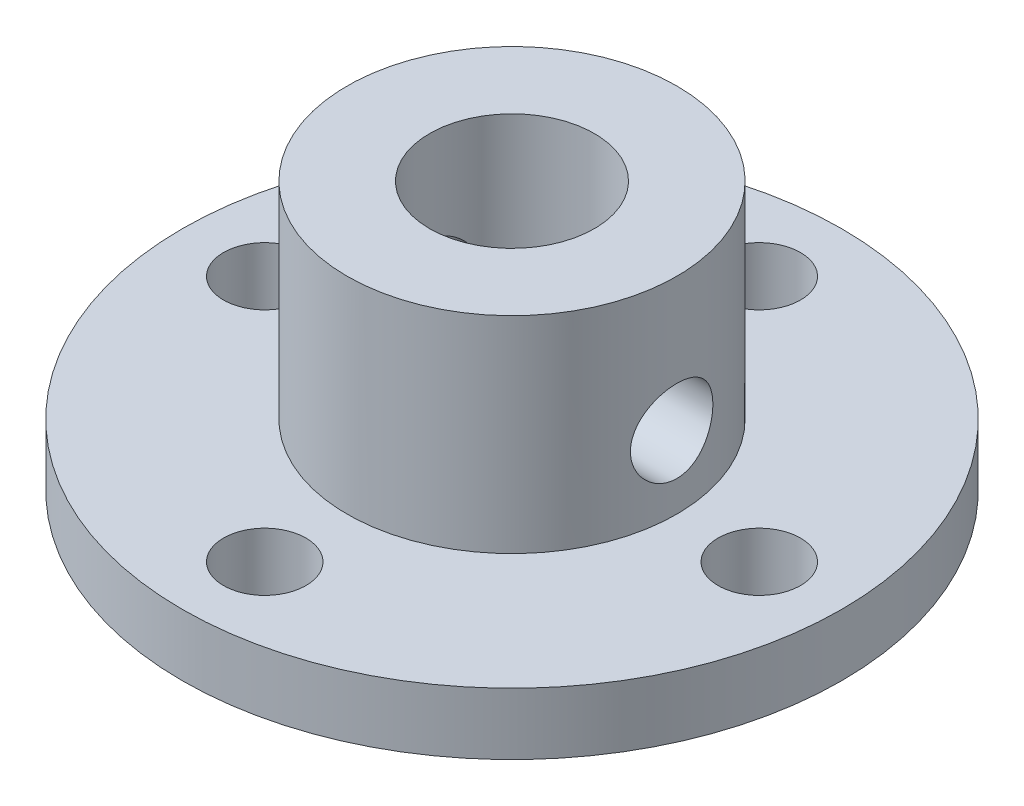
SolidWorks part; units mm, degrees
ref_plane "Front Plane" through (0, 0, 0) normal (0, 0, 1) x (1, 0, 0)
ref_plane "Top Plane" through (0, 0, 0) normal (0, 1, 0) x (1, 0, 0)
ref_plane "Right Plane" through (0, 0, 0) normal (1, 0, 0) x (0, 0, -1)
sketch "Sketch1" plane through (0, 0, 0) normal (0, 1, 0) x (1, 0, 0)
  circle A0 centre (0, 0) radius 4
  circle A1 centre (0, 0) radius 8
  dimension "D1" = 8
  dimension "D2" = 16
extrude "Boss-Extrude1" add sketch "Sketch1" along normal blind 13
sketch "Sketch2" plane through (0, 0, 0) normal (0, -1, 0) x (1, 0, 0)
  line L0 (0, 0) -> (0, 12) construction
  circle A0 centre (0, 0) radius 4
  circle A1 centre (0, 0) radius 16
  circle A2 centre (0, 12) radius 2
  circle A3 centre (12, 0) radius 2
  circle A4 centre (0, -12) radius 2
  circle A5 centre (-12, 0) radius 2
  point P15 (0, 0)
  dimension "D1" = 12
  dimension "D2" = 4
  dimension "D3" = 4
extrude "Boss-Extrude2" add sketch "Sketch2" against normal blind 3
sketch "Sketch4" plane through (0, 13, 0) normal (0, 1, 0) x (1, 0, 0)
  line L0 (0, 4) -> (0, -4) construction
  circle A0 centre (0, 0) radius 4 construction
ref_plane "Plane1" through (0, 0, 0) normal (-1, 0, 0) x (0, 0, 1)
sketch "Sketch5" plane through (0, 0, 0) normal (-1, 0, 0) x (0, 0, 1)
  line L0 (0, 13) -> (0, 0) construction
  line L1 (-4, 13) -> (4, 13) construction
  circle A0 centre (0, 6.5) radius 2
extrude "Cut-Extrude1" cut sketch "Sketch5" against normal blind 14 and the other way blind 11
